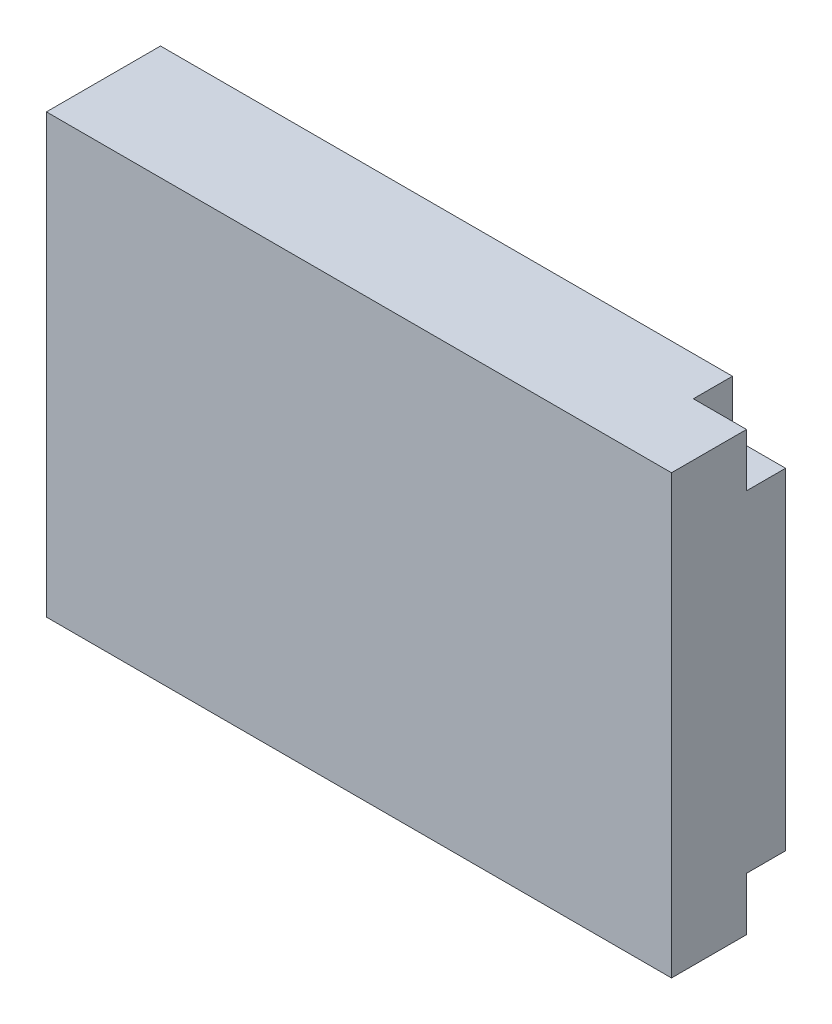
SolidWorks part; units mm, degrees
ref_plane "Ebene vorne" through (0, 0, 0) normal (0, 0, 1) x (1, 0, 0)
ref_plane "Ebene oben" through (0, 0, 0) normal (0, 1, 0) x (1, 0, 0)
ref_plane "Ebene rechts" through (0, 0, 0) normal (1, 0, 0) x (0, 0, -1)
sketch "Skizze1" plane through (0, 0, 0) normal (0, 0, 1) x (1, 0, 0)
  line L1 (-10, -7) -> (10, -7)
  line L2 (-10, -7) -> (-10, 7)
  line L3 (-10, 7) -> (10, 7)
  line L4 (10, -7) -> (10, 7)
  line L5 (-10, -7) -> (10, 7) construction
  line L6 (-10, 7) -> (10, -7) construction
  point P0 (0, 0)
  dimension "D1" = 14
  dimension "D2" = 20
extrude "Aufsatz-Linear austragen1" add sketch "Skizze1" along normal blind 3.65
sketch "Skizze2" plane through (0, 0, 0) normal (0, 0, 1) x (1, 0, 0)
  line L1 (10, 7) -> (8.3, 7)
  line L2 (10, 7) -> (10, 5.3)
  line L3 (10, 5.3) -> (8.3, 5.3)
  line L4 (8.3, 7) -> (8.3, 5.3)
  line L5 (10, -7) -> (8.3, -7)
  line L6 (10, -7) -> (10, -5.3)
  line L7 (10, -5.3) -> (8.3, -5.3)
  line L8 (8.3, -7) -> (8.3, -5.3)
  dimension "D1" = 1.7
extrude "Schnitt-Linear austragen1" cut sketch "Skizze2" along normal blind 1.25
